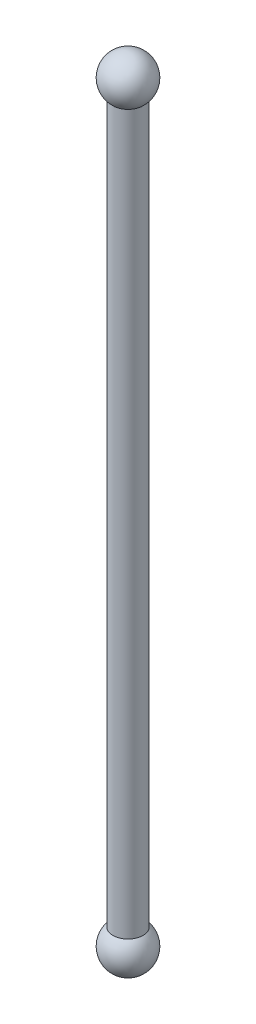
SolidWorks part; units mm, degrees
ref_plane "Front Plane" through (0, 0, 0) normal (0, 0, 1) x (1, 0, 0)
ref_plane "Top Plane" through (0, 0, 0) normal (0, 1, 0) x (1, 0, 0)
ref_plane "Right Plane" through (0, 0, 0) normal (1, 0, 0) x (0, 0, -1)
sketch "Sketch1" plane through (0, 0, 0) normal (0, 0, 1) x (1, 0, 0)
  line L0 (0, -239) -> (0, 239) construction
  line L1 (0, 239) -> (-10, 239)
  line L2 (-10, 239) -> (-10, -239)
  line L3 (-10, -239) -> (0, -239)
  line L4 (0, 239) -> (0, -239)
  point P4 (0, 0)
  dimension "D1" = 10
  dimension "D2" = 478
revolve "Revolve1" add sketch "Sketch1" angle 360 about L0
sketch "Sketch2" plane through (0, 0, 0) normal (0, 0, 1) x (1, 0, 0)
  line L0 (0, 0) -> (0, 265.1803) construction
  line L1 (10, 239) -> (-10, 239) construction
  line L2 (10, 239) -> (-10, 239) construction
  line L3 (-10, 239) -> (0, 239)
  line L4 (0, 265.1803) -> (0, 239)
  arc A0 (0, 265.1803) -> (-10, 239) centre (0, 250.1803) ccw
  dimension "D1" = 30
revolve "Revolve2" add sketch "Sketch2" angle 360 about L0
mirror "Mirror1" about plane through (0, 0, 0) normal (0, 1, 0) of "Revolve2"
